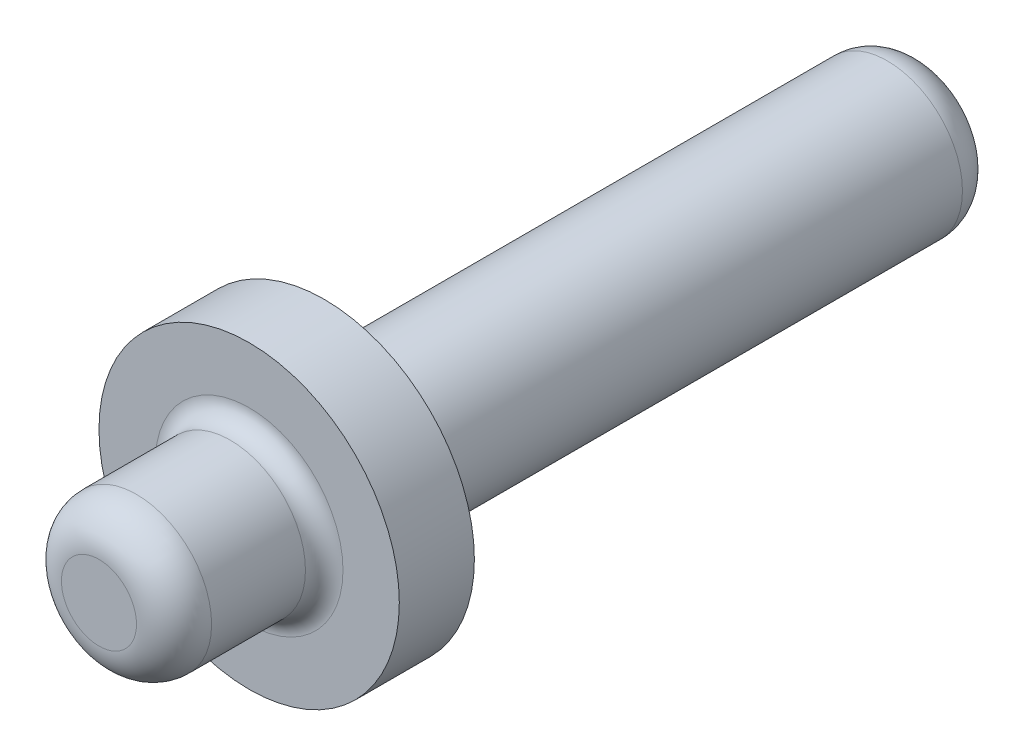
SolidWorks part; units mm, degrees
ref_plane "Front" through (0, 0, 0) normal (0, 0, 1) x (1, 0, 0)
ref_plane "Top" through (0, 0, 0) normal (0, 1, 0) x (1, 0, 0)
ref_plane "Right" through (0, 0, 0) normal (1, 0, 0) x (0, 0, -1)
sketch "Sketch1" plane through (0, 0, 0) normal (0, 0, 1) x (1, 0, 0)
  circle A0 centre (0, 0) radius 3.175
  dimension "D1" = 6.35
extrude "Boss-Extrude1" add sketch "Sketch1" along normal blind 25.4
sketch "Sketch2" plane through (0, 0, 25.4) normal (0, 0, 1) x (1, 0, 0)
  circle A0 centre (0, 0) radius 6.35
  dimension "D1" = 12.7
extrude "Boss-Extrude2" add sketch "Sketch2" along normal blind 3.175
sketch "Sketch3" plane through (0, 0, 28.575) normal (0, 0, 1) x (1, 0, 0)
  circle A0 centre (0, 0) radius 3.175
  dimension "D1" = 6.35
extrude "Boss-Extrude3" add sketch "Sketch3" along normal blind 6.35
fillet "Fillet1" radius 1.5875 2 edges at (3.175, 0, 0) (3.175, 0, 34.925)
fillet "Fillet2" radius 0.7937 2 edges at (3.175, 0, 25.4) (3.175, 0, 28.575)
